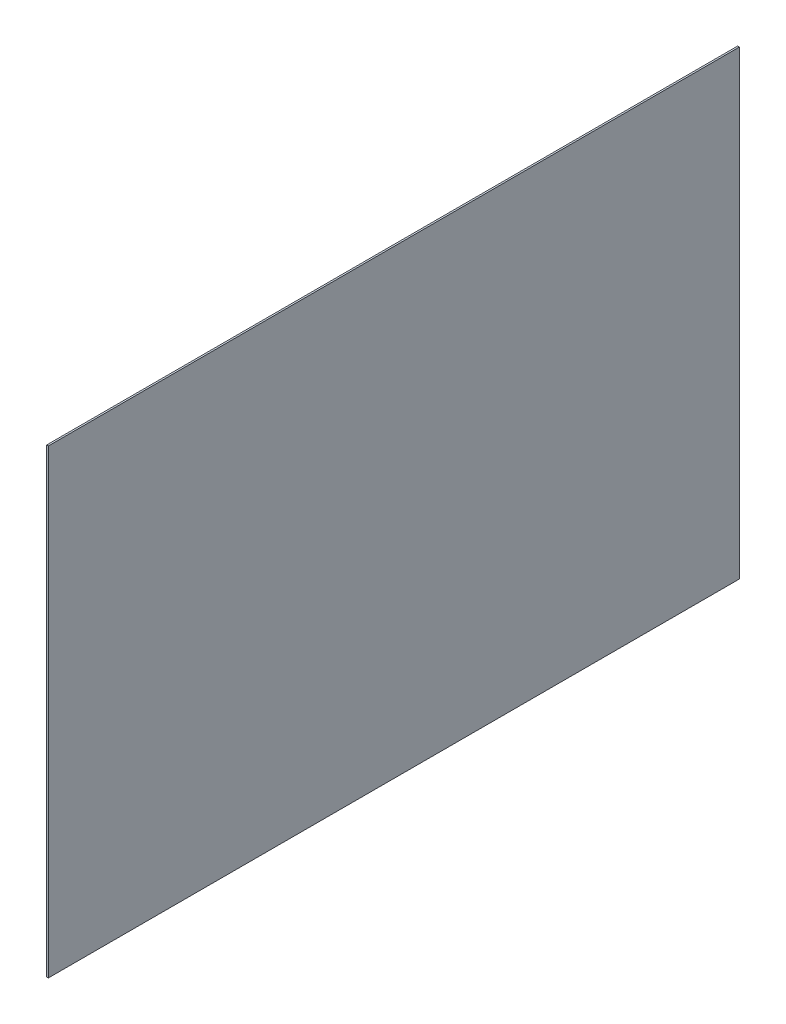
SolidWorks part; units mm, degrees
ref_plane "Спереди" through (0, 0, 0) normal (0, 0, 1) x (1, 0, 0)
ref_plane "Сверху" through (0, 0, 0) normal (0, 1, 0) x (1, 0, 0)
ref_plane "Справа" through (0, 0, 0) normal (1, 0, 0) x (0, 0, -1)
sketch "Эскиз1" plane through (0, 0, 0) normal (1, 0, 0) x (0, 0, -1)
  line L1 (150, -100) -> (-150, -100)
  line L2 (150, -100) -> (150, 100)
  line L3 (150, 100) -> (-150, 100)
  line L4 (-150, -100) -> (-150, 100)
  line L5 (150, -100) -> (-150, 100) construction
  line L6 (150, 100) -> (-150, -100) construction
  point P0 (0, 0)
  dimension "D1" = 300
  dimension "D2" = 200
extrude "Бобышка-Вытянуть1" add sketch "Эскиз1" against normal blind 0.75 contours L3 L4 L1 L2
sketch "Эскиз2" plane through (-0.75, 0, 0) normal (-1, 0, 0) x (0, 0, 1)
  line L1 (148.5, -98.5) -> (-148.5, -98.5)
  line L2 (148.5, -98.5) -> (148.5, 98.5)
  line L3 (148.5, 98.5) -> (-148.5, 98.5)
  line L4 (-148.5, -98.5) -> (-148.5, 98.5)
  line L5 (148.5, -98.5) -> (-148.5, 98.5) construction
  line L6 (148.5, 98.5) -> (-148.5, -98.5) construction
  point P0 (0, 0)
  dimension "D1" = 197
  dimension "D2" = 297
extrude "Бобышка-Вытянуть2" add sketch "Эскиз2" along normal blind 0.75
